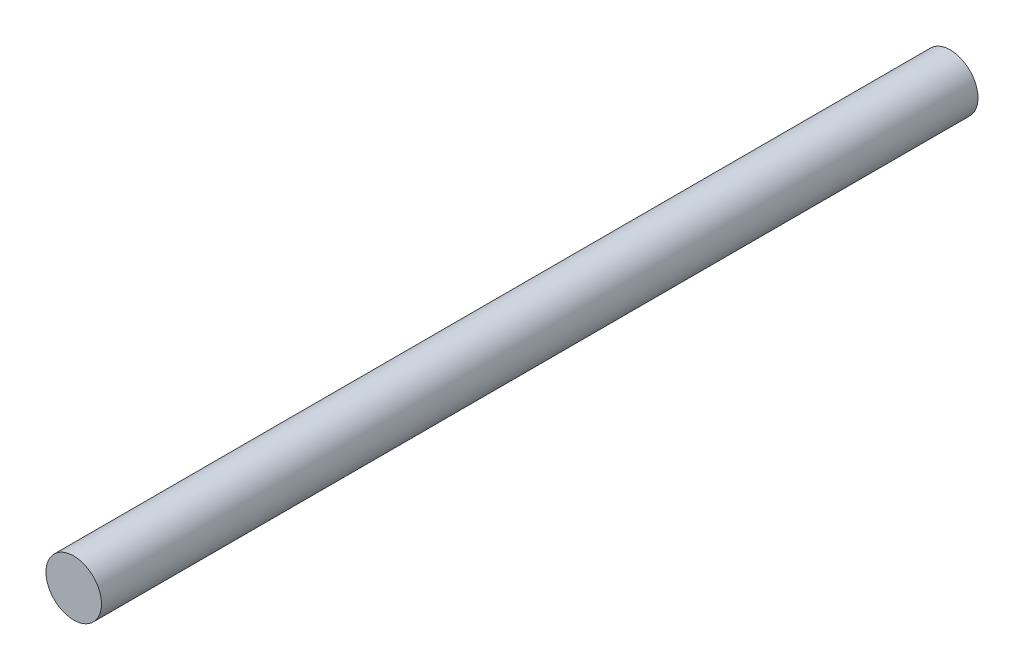
SolidWorks part; units mm, degrees
ref_plane "Спереди" through (0, 0, 0) normal (0, 0, 1) x (1, 0, 0)
ref_plane "Сверху" through (0, 0, 0) normal (0, 1, 0) x (1, 0, 0)
ref_plane "Справа" through (0, 0, 0) normal (1, 0, 0) x (0, 0, -1)
sketch "Эскиз1" plane through (0, 0, 0) normal (0, 0, 1) x (1, 0, 0)
  circle A0 centre (0, 0) radius 3.8
extrude "Бобышка-Вытянуть1" add sketch "Эскиз1" along normal blind 120
